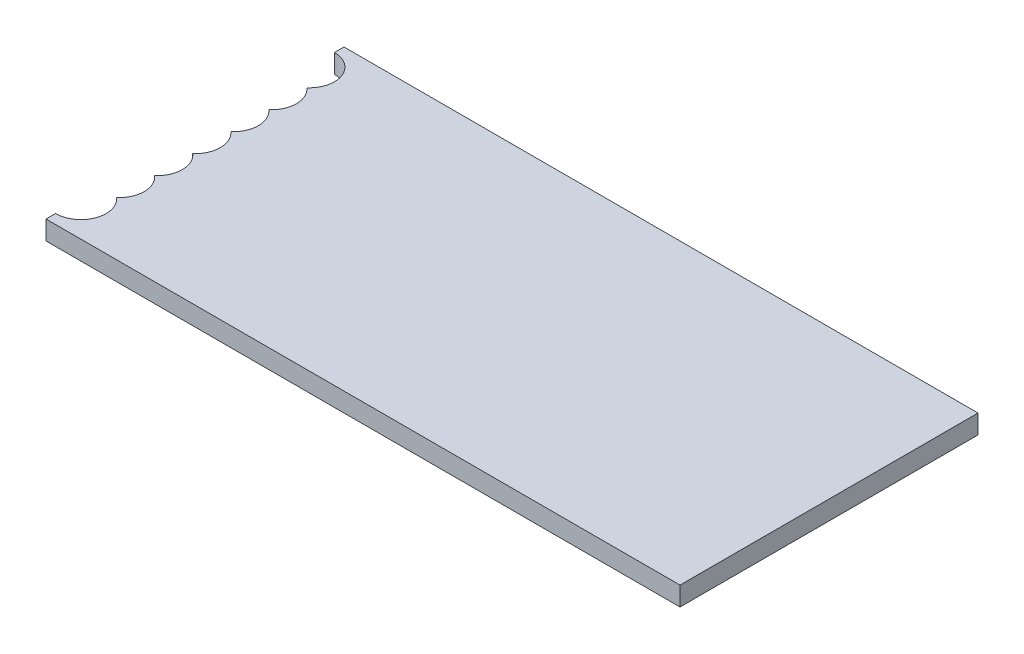
SolidWorks part; units mm, degrees
ref_plane "Спереди" through (0, 0, 0) normal (0, 0, 1) x (1, 0, 0)
ref_plane "Сверху" through (0, 0, 0) normal (0, 1, 0) x (1, 0, 0)
ref_plane "Справа" through (0, 0, 0) normal (1, 0, 0) x (0, 0, -1)
sketch "Эскиз1" plane through (0, 0, 0) normal (0, 1, 0) x (1, 0, 0)
  line L1 (-25, -11.75) -> (25, -11.75)
  line L2 (-25, -11.75) -> (-25, 11.75)
  line L3 (-25, 11.75) -> (25, 11.75)
  line L4 (25, -11.75) -> (25, 11.75)
  line L5 (-25, -11.75) -> (25, 11.75) construction
  line L6 (-25, 11.75) -> (25, -11.75) construction
  point P0 (0, 0)
extrude "Бобышка-Вытянуть1" add sketch "Эскиз1" along normal blind 1.5
sketch "Эскиз2" plane through (0, 1.5, 0) normal (0, 1, 0) x (1, 0, 0)
  line L0 (-25, 11.75) -> (-25, -11.75) construction
  circle A0 centre (-25, 0) radius 2
  circle A1 centre (-25, -3) radius 2
  circle A2 centre (-25, -6) radius 2
  circle A3 centre (-25, -9) radius 2
  circle A4 centre (-25, 0) radius 2
  circle A5 centre (-25, -3) radius 2
  circle A6 centre (-25, -6) radius 2
  circle A7 centre (-25, 3) radius 2
  circle A8 centre (-25, 0) radius 2
  circle A9 centre (-25, -3) radius 2
  circle A10 centre (-25, 6) radius 2
  circle A11 centre (-25, 3) radius 2
  circle A12 centre (-25, 0) radius 2
  circle A13 centre (-25, 3) radius 2
  circle A14 centre (-25, 6) radius 2
  circle A15 centre (-25, 9) radius 2
  line M4 (-25, 11.75) -> (-25, -11.75)
  dimension "D1" = 4
  dimension "D2" = 4
extrude "Вырез-Вытянуть2" cut sketch "Эскиз2" against normal through all contours A14 A15 M4 | A15 A14 M4 | A15 A7 A10 M4 | A10 A7 M4 | A10 A4 A7 M4 | A7 A4 M4 | A7 A1 A0 M4 | A0 A1 M4 | A2 A1 A0 M4 | A1 A2 M4 | A3 A2 A1 M4 | A2 A3 M4 | A3 A2 M4
